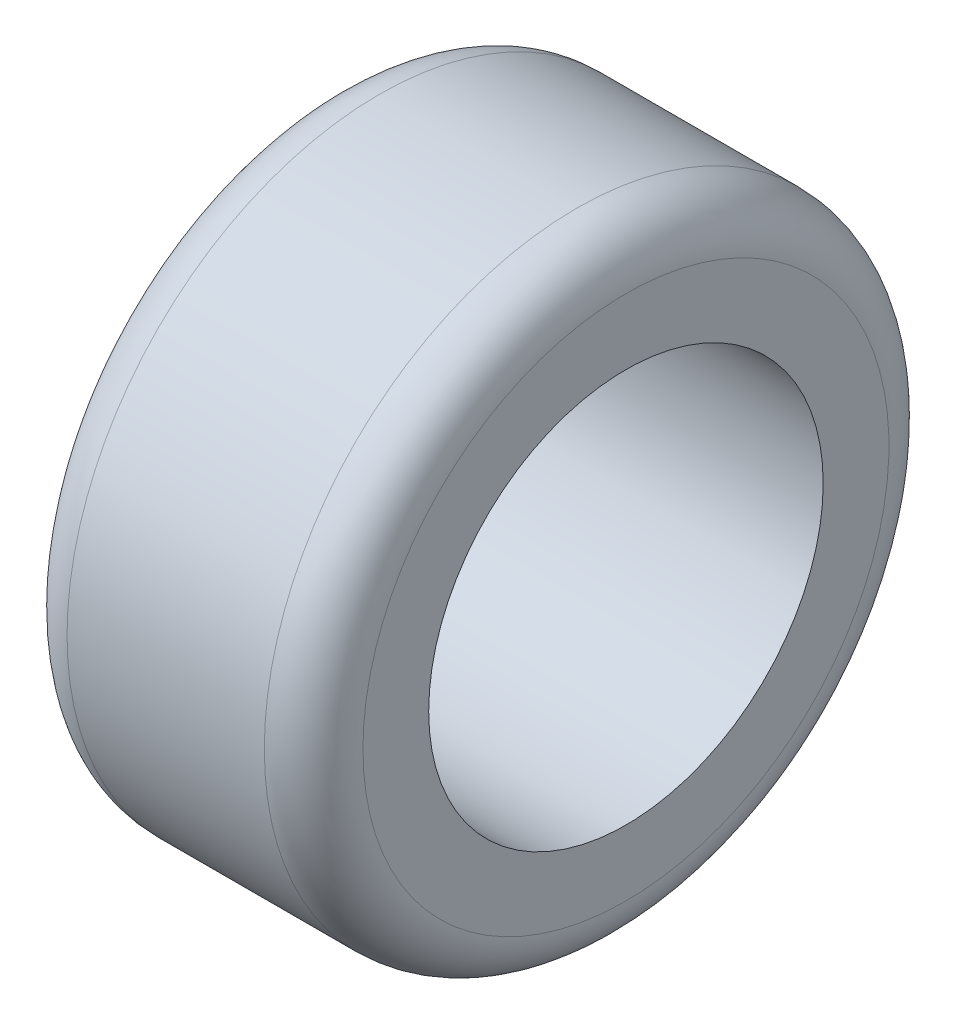
SolidWorks part; units mm, degrees
ref_plane "Спереди" through (0, 0, 0) normal (0, 0, 1) x (1, 0, 0)
ref_plane "Сверху" through (0, 0, 0) normal (0, 1, 0) x (1, 0, 0)
ref_plane "Справа" through (0, 0, 0) normal (1, 0, 0) x (0, 0, -1)
sketch "Эскиз1" plane through (0, 0, 0) normal (0, 0, 1) x (1, 0, 0)
  line L0 (-38.2839, 0) -> (36.5503, 0) construction
  line L1 (-10.5461, 12) -> (7.4539, 12)
  line L3 (-10.5461, 12) -> (-10.5461, 16)
  line L4 (-7.5461, 19) -> (4.4539, 19)
  line L5 (7.4539, 12) -> (7.4539, 16)
  arc A0 (-10.5461, 16) -> (-7.5461, 19) centre (-7.5461, 16) cw
  arc A1 (4.4539, 19) -> (7.4539, 16) centre (4.4539, 16) cw
  point P9 (-10.5461, 19)
  point P12 (7.4539, 19)
  dimension "D1" = 3
  dimension "D2" = 18
  dimension "D3" = 19
revolve "Повернуть1" add sketch "Эскиз1" angle 360 about L0
